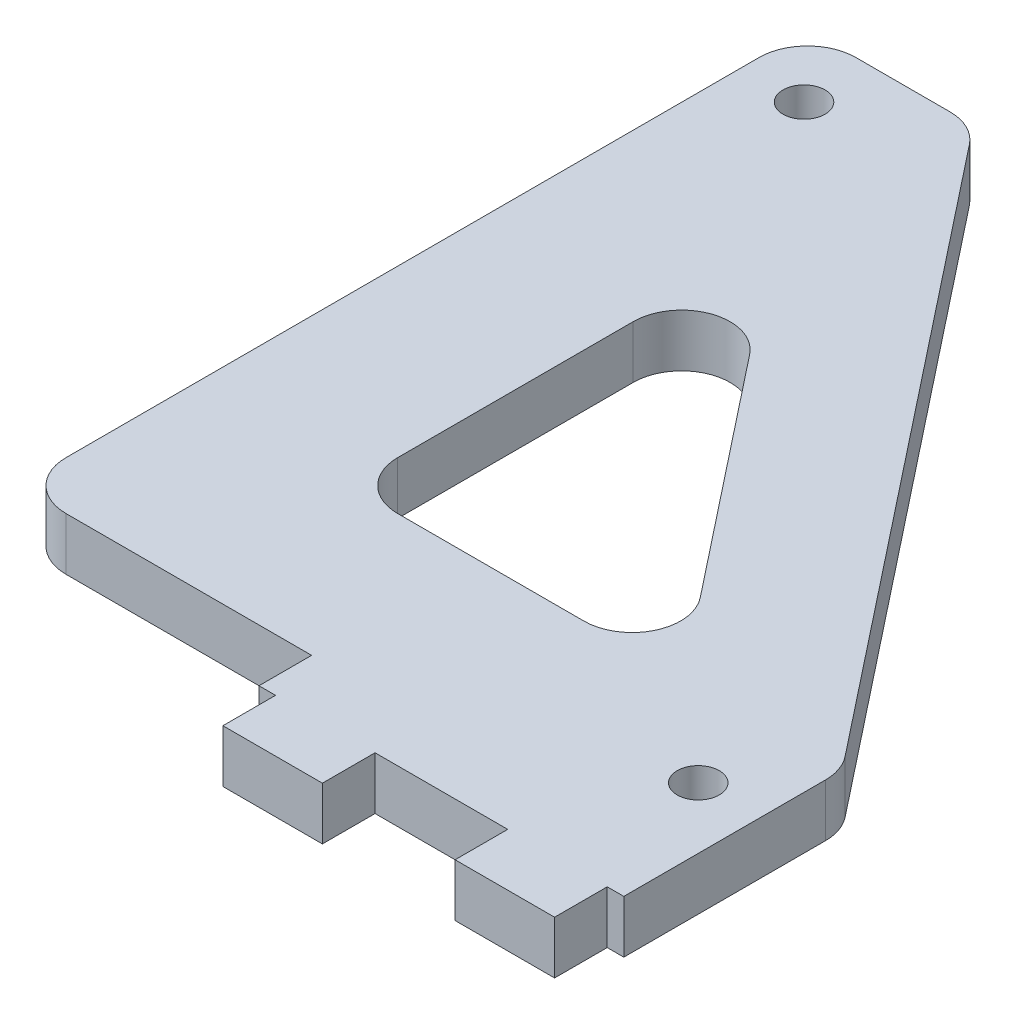
SolidWorks part; units mm, degrees
ref_plane "Front Plane" through (0, 0, 0) normal (0, 0, 1) x (1, 0, 0)
ref_plane "Top Plane" through (0, 0, 0) normal (0, 1, 0) x (1, 0, 0)
ref_plane "Right Plane" through (0, 0, 0) normal (1, 0, 0) x (0, 0, -1)
sketch "Sketch1" plane through (0, 0, 0) normal (0, 1, 0) x (1, 0, 0)
  line L0 (0, 0) -> (0, 47.63)
  line L1 (0, 47.63) -> (10, 47.63)
  line L2 (10, 35.5318) -> (10, 10)
  line L3 (10, 10) -> (30.1717, 10)
  line L4 (39.73, 10) -> (39.73, 0)
  line L5 (39.73, 0) -> (0, 0)
  line L6 (10, 35.5318) -> (30.1717, 10)
  line L7 (10, 47.63) -> (39.73, 10)
  circle A0 centre (3.683, 43.74) radius 1.27
  circle A2 centre (36.043, 5) radius 1.27
  point P14 (0, 0)
  point P15 (0, 0)
  dimension "D5" = 2.54
  dimension "D7" = 32.36
  dimension "D8" = 3.683
  dimension "D9" = 5
  dimension "D6" = 38.74
  dimension "D1" = 39.73
  dimension "D2" = 47.63
  dimension "D3" = 10
  dimension "D4" = 10
  dimension "D11" = 7.5
extrude "Boss-Extrude1" add sketch "Sketch1" along normal blind 3.175
fillet "Fillet1" radius 2.921 7 edges at (0, 1.5875, -47.63) (0, 1.5875, 0) (10, 1.5875, -10) (10, 1.5875, -47.63) (39.73, 1.5875, -10) (10, 1.5875, -35.5318) (30.1717, 1.5875, -10)
sketch "Sketch5" plane through (0, 0, 0) normal (0, 0, 1) x (1, 0, 0)
  line L0 (2.921, 3.175) -> (39.73, 3.175) construction
  line L1 (17.73, 3.175) -> (39.73, 3.175)
  line L2 (17.73, 3.175) -> (17.73, 0)
  line L3 (17.73, 0) -> (39.73, 0)
  line L4 (39.73, 3.175) -> (39.73, 0)
  line L5 (2.921, 0) -> (39.73, 0) construction
  line L7 (39.73, 3.175) -> (39.73, 0) construction
  dimension "D1" = 22
extrude "Boss-Extrude3" add sketch "Sketch5" along normal blind 3.175
sketch "Sketch2" plane through (0, 0, 3.175) normal (0, 0, 1) x (1, 0, 0)
  line L0 (2.921, 3.175) -> (17.73, 3.175) construction
  line L1 (18.73, 3.175) -> (24.73, 3.175)
  line L2 (18.73, 3.175) -> (18.73, 0)
  line L3 (18.73, 0) -> (24.73, 0)
  line L4 (24.73, 3.175) -> (24.73, 0)
  line L5 (2.921, 0) -> (17.73, 0) construction
  line L6 (17.73, 1.5875) -> (18.73, 1.5875) construction
  line L7 (32.73, 3.175) -> (38.73, 3.175)
  line L8 (32.73, 3.175) -> (32.73, 0)
  line L9 (32.73, 0) -> (38.73, 0)
  line L10 (38.73, 3.175) -> (38.73, 0)
  line L11 (17.73, 3.175) -> (17.73, 0) construction
  line L12 (38.73, 1.5875) -> (39.73, 1.5875) construction
  line L13 (39.73, 0) -> (39.73, 3.175) construction
  dimension "D1" = 6
  dimension "D2" = 6
  dimension "D3" = 20
extrude "Boss-Extrude2" add sketch "Sketch2" along normal blind 3.175
